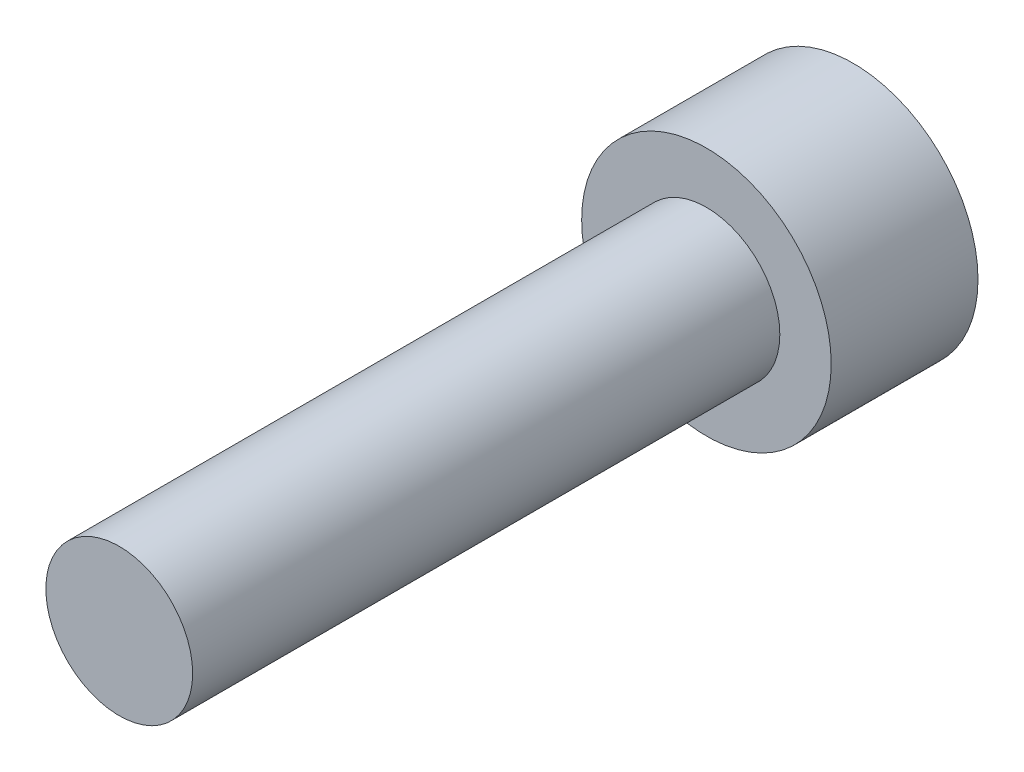
SolidWorks part; units mm, degrees
ref_plane "正面" through (0, 0, 0) normal (0, 0, 1) x (1, 0, 0)
ref_plane "平面" through (0, 0, 0) normal (0, 1, 0) x (1, 0, 0)
ref_plane "右側面" through (0, 0, 0) normal (1, 0, 0) x (0, 0, -1)
sketch "ｽｹｯﾁ1" plane through (0, 0, 0) normal (0, 0, 1) x (1, 0, 0)
  circle A0 centre (0, 0) radius 4.25
  dimension "D1" = 8.5
extrude "ﾎﾞｽ - 押し出し1" add sketch "ｽｹｯﾁ1" along normal blind 5
sketch "ｽｹｯﾁ2" plane through (0, 0, 5) normal (0, 0, 1) x (1, 0, 0)
  circle A0 centre (0, 0) radius 2.5
  dimension "D1" = 5
extrude "ﾎﾞｽ - 押し出し2" add sketch "ｽｹｯﾁ2" along normal blind 20
cosmetic thread "ねじ山1" parameters "D2"=3
sketch "ｽｹｯﾁ3" plane through (0, 0, 0) normal (0, 0, -1) x (-1, 0, 0)
  line L1 (2.4812, -1.1109) -> (2.2027, 1.5934)
  line L2 (2.2027, 1.5934) -> (-0.2785, 2.7043)
  line L3 (-0.2785, 2.7043) -> (-2.4812, 1.1109)
  line L4 (-2.4812, 1.1109) -> (-2.2027, -1.5934)
  line L5 (-2.2027, -1.5934) -> (0.2785, -2.7043)
  line L6 (0.2785, -2.7043) -> (2.4812, -1.1109)
  circle A0 centre (0, 0) radius 2.3544 construction
extrude "ｶｯﾄ - 押し出し1" cut sketch "ｽｹｯﾁ3" against normal blind 2
